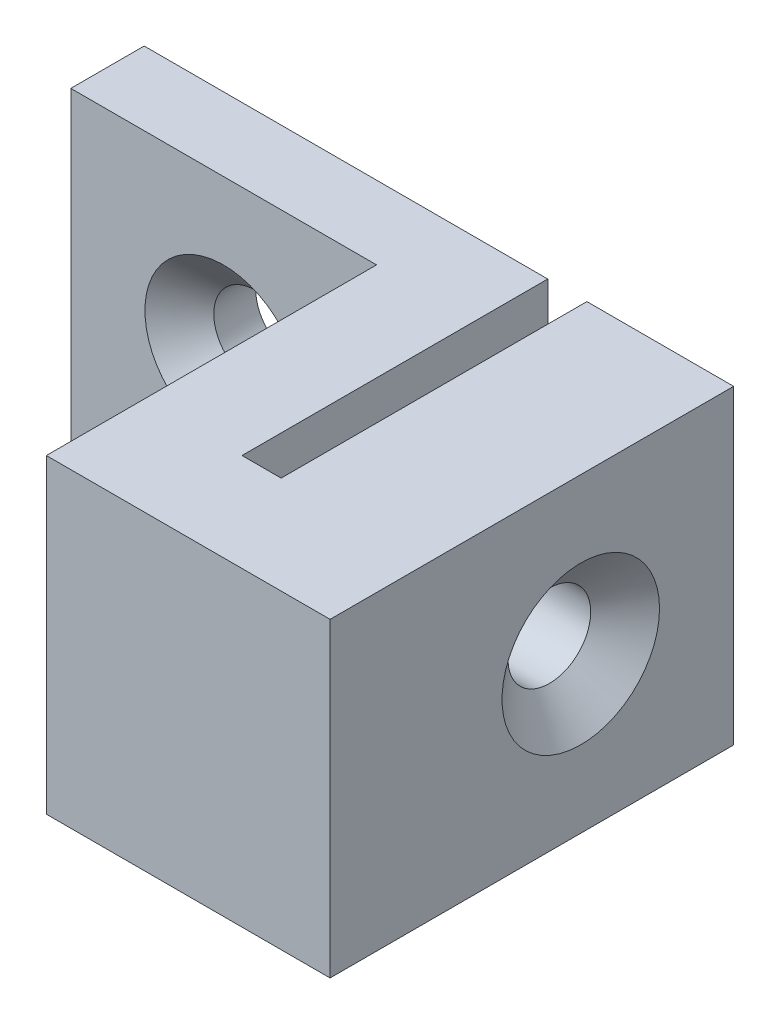
SolidWorks part; units mm, degrees
ref_plane "Front Plane" through (0, 0, 0) normal (0, 0, 1) x (1, 0, 0)
ref_plane "Top Plane" through (0, 0, 0) normal (0, 1, 0) x (1, 0, 0)
ref_plane "Right Plane" through (0, 0, 0) normal (1, 0, 0) x (0, 0, -1)
sketch "Sketch1" plane through (0, 0, 0) normal (0, 1, 0) x (1, 0, 0)
  line L0 (-1.6, 0) -> (1.6, 0)
  line L1 (1.6, 0) -> (1.6, 25)
  line L2 (1.6, 25) -> (13.6, 25)
  line L3 (13.6, 25) -> (13.6, -8)
  line L4 (13.6, -8) -> (-9.6, -8)
  line L5 (-9.6, -8) -> (-9.6, 19)
  line L6 (-9.6, 19) -> (-34.6, 19)
  line L7 (-34.6, 19) -> (-34.6, 25)
  line L8 (-34.6, 25) -> (-1.6, 25)
  line L9 (-1.6, 25) -> (-1.6, 0)
  point P4 (0, 0)
  dimension "D1" = 3.2
  dimension "D2" = 12
  dimension "D3" = 8
  dimension "D4" = 8
  dimension "D5" = 25
  dimension "D6" = 6
  dimension "D7" = 25
extrude "Boss-Extrude1" add sketch "Sketch1" along normal blind 25.4
hole_wizard "1/4-20 Tapped Hole1" positions "Sketch2" profile "Sketch3" tap size "1/4-20" standard "ANSI Inch"
sketch "Sketch2" plane through (-1.6, 0, 0) normal (1, 0, 0) x (0, 0, -1)
  line L0 (12.5, 25.4) -> (12.5, 0) construction
  line L1 (0, 25.4) -> (25, 25.4) construction
  line L2 (0, 0) -> (25, 0) construction
  point P0 (12.5, 12.7)
sketch "Sketch3" plane through (-1.6, 12.7, -12.5) normal (0, 1, 0) x (0, 0, -1)
  line L0 (0, 0) -> (0, 18.0438)
  line L1 (0, 18.0438) -> (2.5527, 16.51)
  line L2 (2.5527, 16.51) -> (2.5527, 0)
  line L5 (2.5527, 0) -> (0, 0)
  line L10 (0, 18.0438) -> (-2.5527, 16.51) construction
  line L11 (0, -6.35) -> (0, 107.95) construction
  dimension "Tap Drill Dia." = 5.1054
  dimension "Tap Drill Depth" = 16.51
  dimension "Drill Angle" = 118
cosmetic thread "Hole Thread1" parameters "D1"=12.7, "D2"=6.35
hole_wizard "CSK for 1/4 Flat Head Machine Screw (100)1" positions "Sketch6" profile "Sketch7" countersink size "1/4" standard "ANSI Inch"
sketch "Sketch6" plane through (13.6, 0, 0) normal (1, 0, 0) x (0, 0, -1)
  point P0 (12.5, 12.7)
sketch "Sketch7" plane through (13.6, 12.7, -12.5) normal (0, 1, 0) x (0, 0, -1)
  line L0 (0, 0) -> (0, 18.5398)
  line L1 (0, 18.5398) -> (3.3782, 16.51)
  line L2 (3.3782, 16.51) -> (3.3782, 2.5682)
  line L3 (3.3782, 2.5682) -> (6.4389, 0)
  line L5 (6.4389, 0) -> (0, 0)
  line L6 (-3.3782, 2.5682) -> (-6.4389, 0) construction
  line L10 (0, 18.5398) -> (-3.3782, 16.51) construction
  line L11 (0, -6.35) -> (0, 107.95) construction
  dimension "Hole Dia." = 6.7564
  dimension "Hole Depth" = 16.51
  dimension "Near C'Sink Dia." = 12.8778
  dimension "Near C'Sink Angle" = 100
  dimension "Drill Angle" = 118
hole_wizard "CSK for 1/4 Flat Head Machine Screw (100)2" positions "Sketch8" profile "Sketch9" countersink size "1/4" standard "ANSI Inch"
sketch "Sketch8" plane through (0, 0, -19) normal (0, 0, 1) x (1, 0, 0)
  line L0 (-22.1, 25.4) -> (-22.1, 0) construction
  line L1 (-34.6, 25.4) -> (-9.6, 25.4) construction
  line L2 (-34.6, 0) -> (-9.6, 0) construction
  point P0 (-22.1, 12.7)
  point P12 (-22.1, 12.7)
sketch "Sketch9" plane through (-22.1, 12.7, -19) normal (1, 0, 0) x (0, -1, 0)
  line L0 (0, 0) -> (0, 18.5398)
  line L1 (0, 18.5398) -> (3.3782, 16.51)
  line L2 (3.3782, 16.51) -> (3.3782, 2.5682)
  line L3 (3.3782, 2.5682) -> (6.4389, 0)
  line L5 (6.4389, 0) -> (0, 0)
  line L6 (-3.3782, 2.5682) -> (-6.4389, 0) construction
  line L10 (0, 18.5398) -> (-3.3782, 16.51) construction
  line L11 (0, -6.35) -> (0, 107.95) construction
  dimension "Hole Dia." = 6.7564
  dimension "Hole Depth" = 16.51
  dimension "Near C'Sink Dia." = 12.8778
  dimension "Near C'Sink Angle" = 100
  dimension "Drill Angle" = 118
